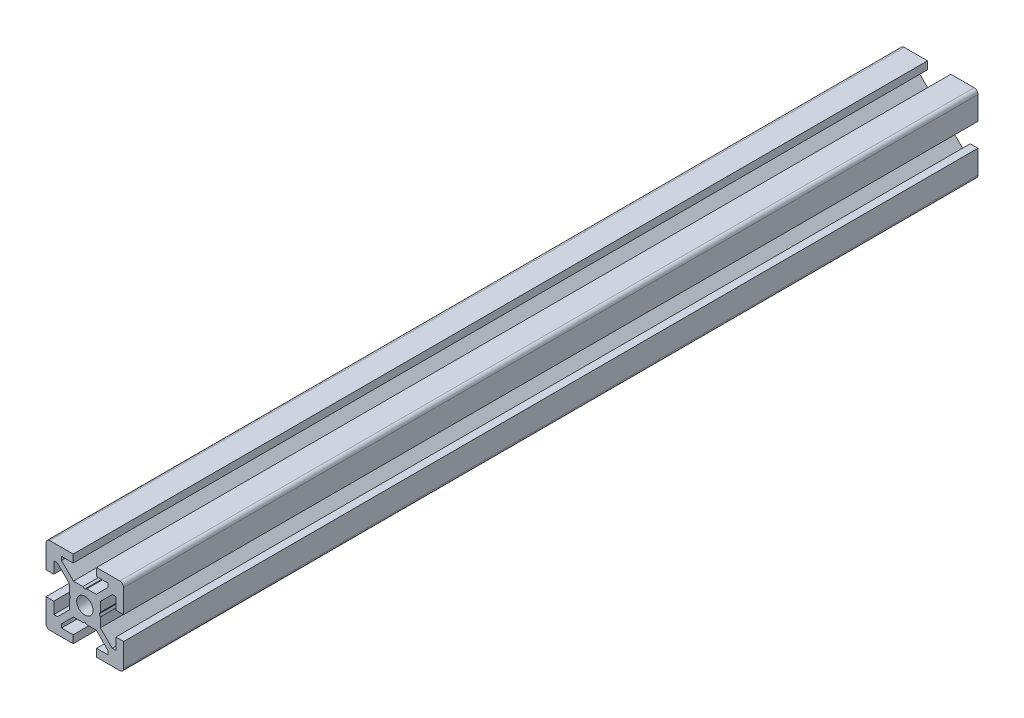
SolidWorks part; units mm, degrees
ref_plane "정면" through (0, 0, 0) normal (0, 0, 1) x (1, 0, 0)
ref_plane "윗면" through (0, 0, 0) normal (0, 1, 0) x (1, 0, 0)
ref_plane "우측면" through (0, 0, 0) normal (1, 0, 0) x (0, 0, -1)
sketch "Model" plane through (0, 0, 0) normal (0, 0, 1) x (1, 0, 0)
  line L0 (-10, 3) -> (-8, 3)
  line L1 (-10, 9) -> (-10, 3)
  line L2 (-3, 10) -> (-9, 10)
  line L3 (-3, 8) -> (-3, 10)
  line L4 (-6, 8) -> (-3, 8)
  line L5 (-6, 7.0607) -> (-6, 8)
  line L6 (-2.9393, 4) -> (-6, 7.0607)
  line L7 (-0.5196, 4) -> (-2.9393, 4)
  line L8 (0, 3.7) -> (-0.5196, 4)
  line L9 (0.5196, 4) -> (0, 3.7)
  line L10 (2.9393, 4) -> (0.5196, 4)
  line L11 (6, 7.0607) -> (2.9393, 4)
  line L12 (6, 8) -> (6, 7.0607)
  line L13 (3, 8) -> (6, 8)
  line L14 (3, 10) -> (3, 8)
  line L15 (9, 10) -> (3, 10)
  line L16 (10, 3) -> (10, 9)
  line L17 (8, 3) -> (10, 3)
  line L18 (8, 6) -> (8, 3)
  line L19 (7.0607, 6) -> (8, 6)
  line L20 (4, 2.9393) -> (7.0607, 6)
  line L21 (4, 0.5196) -> (4, 2.9393)
  line L22 (3.7, 0) -> (4, 0.5196)
  line L23 (4, -0.5196) -> (3.7, 0)
  line L24 (4, -2.9393) -> (4, -0.5196)
  line L25 (7.0607, -6) -> (4, -2.9393)
  line L26 (8, -6) -> (7.0607, -6)
  line L27 (8, -3) -> (8, -6)
  line L28 (10, -3) -> (8, -3)
  line L29 (10, -9) -> (10, -3)
  line L30 (3, -10) -> (9, -10)
  line L31 (3, -8) -> (3, -10)
  line L32 (6, -8) -> (3, -8)
  line L33 (6, -7.0607) -> (6, -8)
  line L34 (2.9393, -4) -> (6, -7.0607)
  line L35 (0.5196, -4) -> (2.9393, -4)
  line L36 (0, -3.7) -> (0.5196, -4)
  line L37 (-0.5196, -4) -> (0, -3.7)
  line L38 (-2.9393, -4) -> (-0.5196, -4)
  line L39 (-6, -7.0607) -> (-2.9393, -4)
  line L40 (-6, -8) -> (-6, -7.0607)
  line L41 (-3, -8) -> (-6, -8)
  line L42 (-3, -10) -> (-3, -8)
  line L43 (-9, -10) -> (-3, -10)
  line L44 (-10, -3) -> (-10, -9)
  line L45 (-8, -3) -> (-10, -3)
  line L46 (-8, -6) -> (-8, -3)
  line L47 (-7.0607, -6) -> (-8, -6)
  line L48 (-4, -2.9393) -> (-7.0607, -6)
  line L49 (-4, -0.5196) -> (-4, -2.9393)
  line L50 (-3.7, 0) -> (-4, -0.5196)
  line L51 (-4, 0.5196) -> (-3.7, 0)
  line L52 (-4, 2.9393) -> (-4, 0.5196)
  line L53 (-7.0607, 6) -> (-4, 2.9393)
  line L54 (-8, 6) -> (-7.0607, 6)
  line L55 (-8, 3) -> (-8, 6)
  arc A0 (-9, 10) -> (-10, 9) centre (-9, 9) ccw
  arc A1 (10, 9) -> (9, 10) centre (9, 9) ccw
  arc A2 (9, -10) -> (10, -9) centre (9, -9) ccw
  arc A3 (-10, -9) -> (-9, -10) centre (-9, -9) ccw
  circle A4 centre (0, 0) radius 2.1
  point P66 (0, 0)
  dimension "D1" = 4.2
extrude "보스-돌출1" add sketch "Model" along normal blind 220
